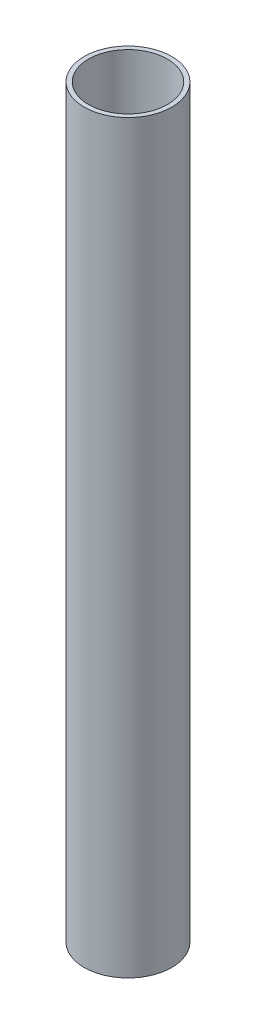
SolidWorks part; units mm, degrees
ref_plane "Front Plane" through (0, 0, 0) normal (0, 0, 1) x (1, 0, 0)
ref_plane "Top Plane" through (0, 0, 0) normal (0, 1, 0) x (1, 0, 0)
ref_plane "Right Plane" through (0, 0, 0) normal (1, 0, 0) x (0, 0, -1)
sketch "Sketch1" plane through (0, 0, 0) normal (0, 1, 0) x (1, 0, 0)
  circle A0 centre (0, 0) radius 10
  circle A2 centre (0, 0) radius 9
  dimension "D1" = 20
  dimension "D2" = 1
extrude "Boss-Extrude1" add sketch "Sketch1" along normal blind 170
